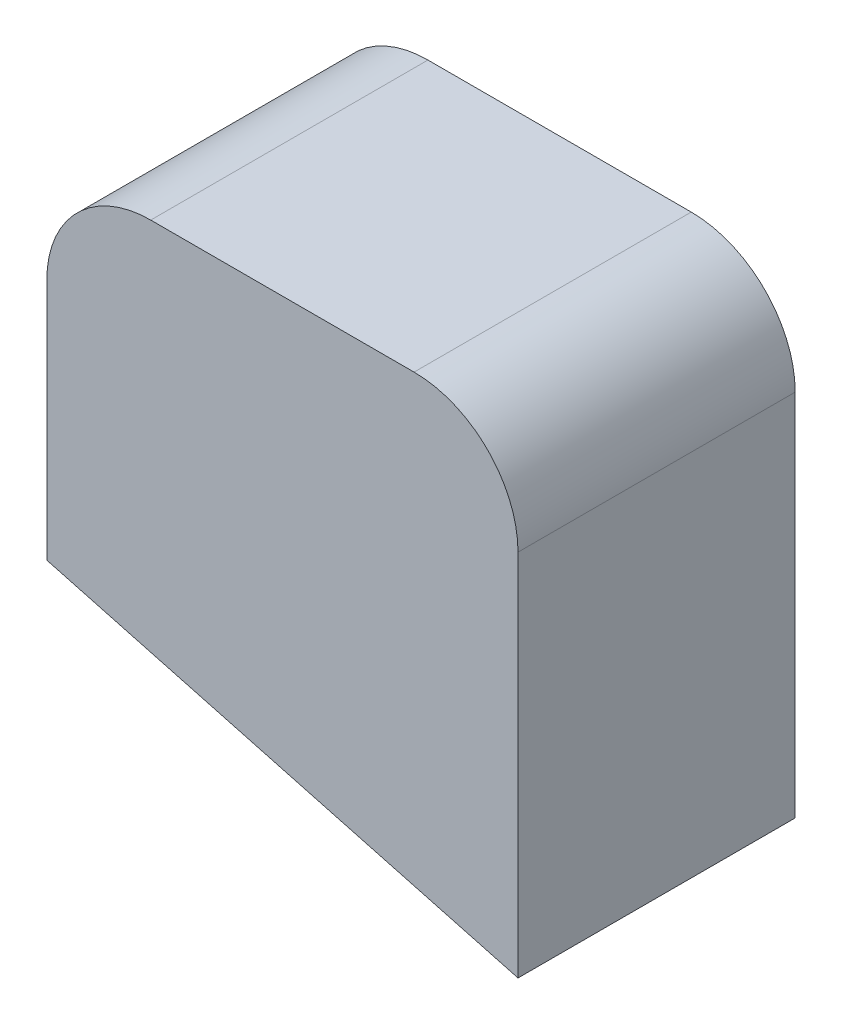
SolidWorks part; units mm, degrees
ref_plane "Alzado" through (0, 0, 0) normal (0, 0, 1) x (1, 0, 0)
ref_plane "Planta" through (0, 0, 0) normal (0, 1, 0) x (1, 0, 0)
ref_plane "Vista lateral" through (0, 0, 0) normal (1, 0, 0) x (0, 0, -1)
sketch "Croquis1" plane through (0, 0, 0) normal (0, 0, 1) x (1, 0, 0)
  line L0 (0, 0) -> (-13.6, 3.6441)
  line L1 (-13.6, 3.6441) -> (-13.6, 13.6441)
  line L2 (0, 34.3421) -> (0, 0)
  line L3 (0, 0) -> (-164.6672, 0) construction
  line L4 (-13.6, 13.6441) -> (0, 13.6441)
  line L5 (0, 13.6441) -> (0, 34.3421)
  dimension "D1" = 15
  dimension "D2" = 10
  dimension "D3" = 13.6
extrude "Saliente-Extruir1" add sketch "Croquis1" along normal blind 8 contours L4 L1 L0 L2
fillet "Redondeo1" radius 3 2 edges at (0, 13.6441, 4) (-13.6, 13.6441, 4)
